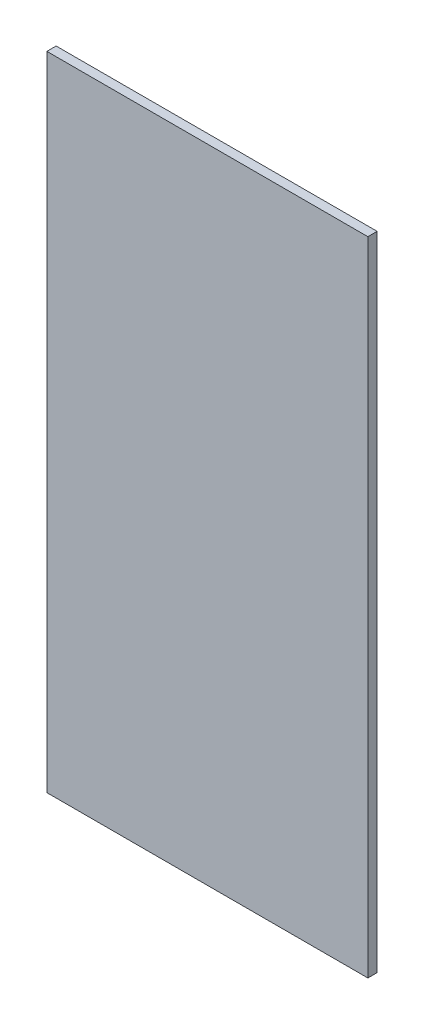
SolidWorks part; units mm, degrees
ref_plane "Front Plane" through (0, 0, 0) normal (0, 0, 1) x (1, 0, 0)
ref_plane "Top Plane" through (0, 0, 0) normal (0, 1, 0) x (1, 0, 0)
ref_plane "Right Plane" through (0, 0, 0) normal (1, 0, 0) x (0, 0, -1)
sketch "Sketch1" plane through (0, 0, 0) normal (0, 0, 1) x (1, 0, 0)
  line L0 (0, 165.1) -> (0, -165.1) construction
  line L1 (-82.55, 165.1) -> (82.55, 165.1)
  line L2 (-82.55, 165.1) -> (-82.55, -165.1)
  line L3 (-82.55, -165.1) -> (82.55, -165.1)
  line L4 (82.55, 165.1) -> (82.55, -165.1)
  point P6 (0, 0)
  dimension "D1" = 165.1
  dimension "D2" = 330.2
extrude "Boss-Extrude1" add sketch "Sketch1" along normal blind 4.7625
equation "\"Height\"= 12in"
equation "\"Depth\"= 7in"
equation "\"WallThickness\"= 0.1875in"
equation "\"FloorThickness\"= 0.1875in"
equation "\"D1@Boss-Extrude1\"=\"WallThickness\""
